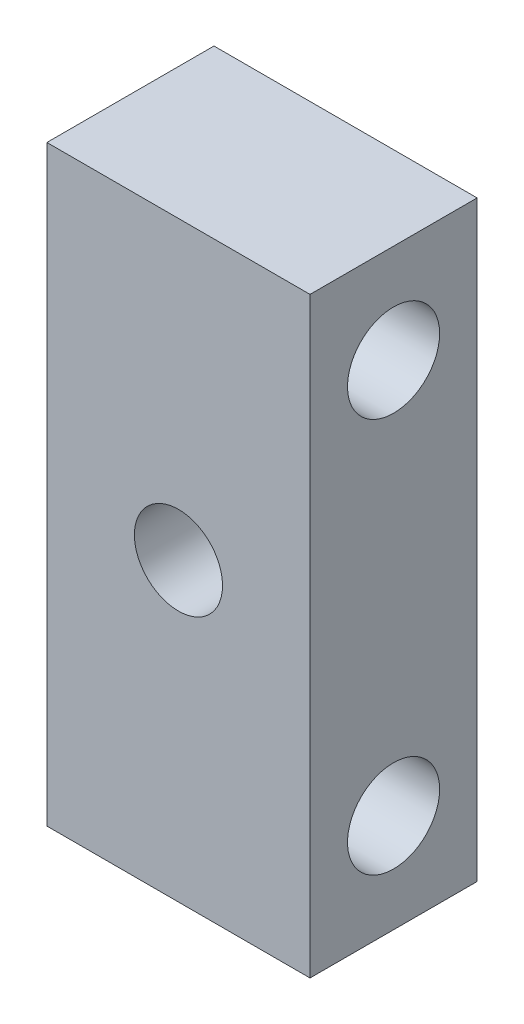
SolidWorks part; units mm, degrees
ref_plane "Front Plane" through (0, 0, 0) normal (0, 0, 1) x (1, 0, 0)
ref_plane "Top Plane" through (0, 0, 0) normal (0, 1, 0) x (1, 0, 0)
ref_plane "Right Plane" through (0, 0, 0) normal (1, 0, 0) x (0, 0, -1)
sketch "Sketch1" plane through (0, 0, 0) normal (0, 0, 1) x (1, 0, 0)
  line L5 (10, 22.5) -> (-10, 22.5)
  line L6 (10, 22.5) -> (10, -22.5)
  line L7 (10, -22.5) -> (-10, -22.5)
  line L8 (-10, 22.5) -> (-10, -22.5)
  line L9 (0, -22.5) -> (0, 22.5) construction
  line L10 (10, 0) -> (-10, 0) construction
  point P0 (0, 0)
  point P1 (0, 0)
  dimension "D1" = 45
  dimension "D2" = 20
extrude "Boss-Extrude1" add sketch "Sketch1" along normal blind 12.7
sketch "Sketch2" plane through (0, 0, 12.7) normal (0, 0, 1) x (1, 0, 0)
  circle A0 centre (0, 0) radius 3.35
extrude "Cut-Extrude1" cut sketch "Sketch2" against normal through all
sketch "Sketch3" plane through (10, 0, 0) normal (1, 0, 0) x (0, 0, -1)
  circle A0 centre (-6.35, 15) radius 3.5
  circle A1 centre (-6.35, -15) radius 3.5
extrude "Cut-Extrude2" cut sketch "Sketch3" against normal through all
